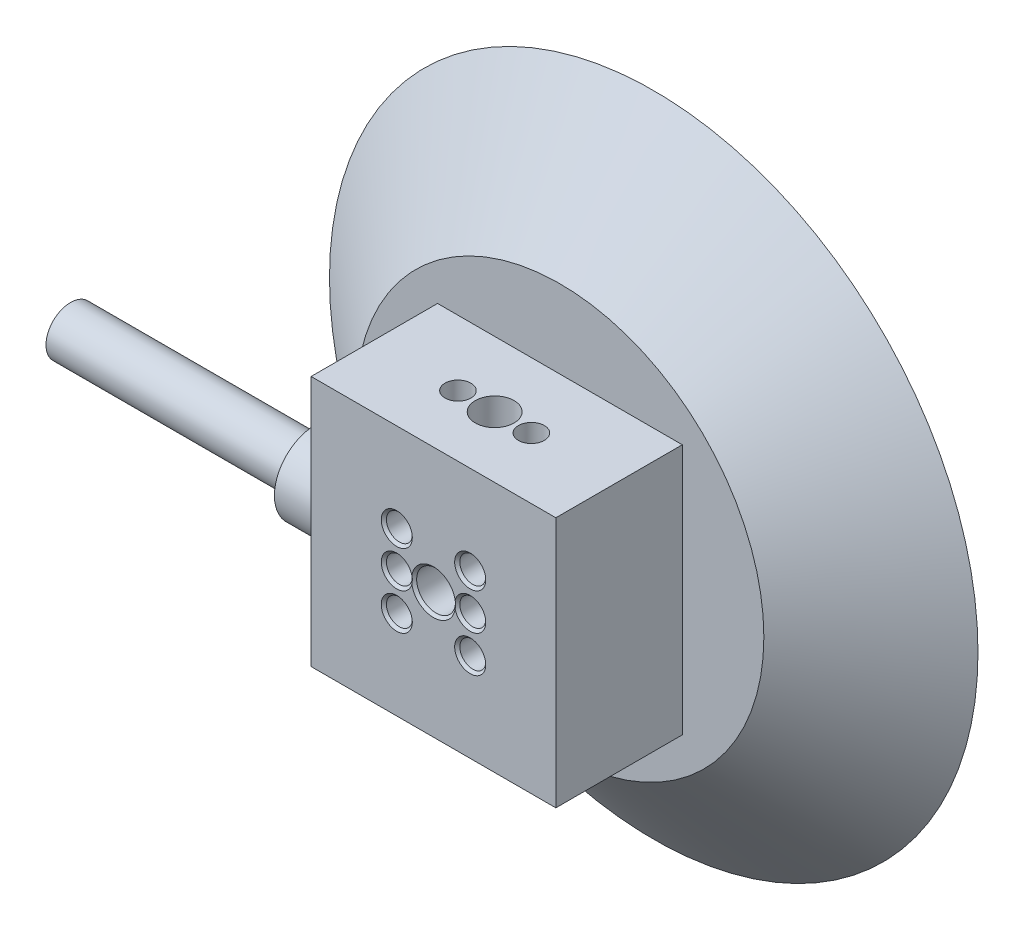
SolidWorks part; units mm, degrees
ref_plane "前视基准面" through (0, 0, 0) normal (0, 0, 1) x (1, 0, 0)
ref_plane "上视基准面" through (0, 0, 0) normal (0, 1, 0) x (1, 0, 0)
ref_plane "右视基准面" through (0, 0, 0) normal (1, 0, 0) x (0, 0, -1)
sketch "草图2" plane through (0, 0, 0) normal (0, 0, 1) x (1, 0, 0)
  circle A0 centre (0, 0) radius 79.5
  dimension "D1" = 159
ref_plane "基准面4" through (0, 0, 23) normal (0, 0, 1) x (1, 0, 0)
sketch "草图3" plane through (0, 0, 23) normal (0, 0, 1) x (1, 0, 0)
  circle A0 centre (0, 0) radius 50
  dimension "D1" = 100
loft "放样1" add profiles "草图2", "草图3"
sketch "草图4" plane through (0, 0, 23) normal (0, 0, 1) x (1, 0, 0)
  line L0 (0, 0) -> (0, -66.3516) construction
  line L1 (0, 0) -> (-87.6409, 0) construction
  line L3 (-30, 30.8) -> (30, 30.8)
  line L4 (-30, 30.8) -> (-30, -30.8)
  line L5 (-30, -30.8) -> (30, -30.8)
  line L6 (30, 30.8) -> (30, -30.8)
  dimension "D1" = 61.6
  dimension "D2" = 60
extrude "凸台-拉伸1" add sketch "草图4" along normal blind 31
sketch "草图5" plane through (-30, 0, 0) normal (-1, 0, 0) x (0, 0, 1)
  line L0 (23, 10) -> (43, 10)
  line L1 (23, -50) -> (23, 50) construction
  line L2 (20, 0) -> (77.0997, 0) construction
  line L3 (23, -10) -> (43, -10)
  line L4 (23, 10) -> (23, -10)
  arc A0 (43, -10) -> (43, 10) centre (43, 0) ccw
  dimension "D2" = 10
  dimension "D1" = 10
  dimension "D3" = 20
extrude "凸台-拉伸2" add sketch "草图5" along normal blind 10
sketch "草图6" plane through (-40, 0, 0) normal (-1, 0, 0) x (0, 0, 1)
  circle A0 centre (43, 0) radius 6
  dimension "D1" = 12
extrude "凸台-拉伸3" add sketch "草图6" along normal blind 60
hole_wizard "3/8 (0.375) 直径孔1" positions "草图7" profile "草图8" hole size "3/8" standard "ANSI Inch" end condition through all
sketch "草图7" plane through (0, 0, 54) normal (0, 0, 1) x (1, 0, 0)
  point P0 (0, 0)
sketch "草图8" plane through (0, 0, 54) normal (1, 0, 0) x (0, -1, 0)
  line L0 (0, 0) -> (0, 54.0001)
  line L1 (0, 54.0001) -> (4.7625, 54.0001)
  line L2 (4.7625, 54.0001) -> (4.7625, 0.635)
  line L3 (4.7625, 0.635) -> (5.3975, 0)
  line L5 (5.3975, 0) -> (0, 0)
  line L6 (-4.7625, 0.635) -> (-5.3975, 0) construction
  line L11 (0, -6.35) -> (0, 107.95) construction
  dimension "通孔孔直径" = 9.525
  dimension "通孔孔深度" = 54.0001
  dimension "近端锥形沉头孔直径" = 10.795
  dimension "近端锥形沉头孔角度" = 90
hole_wizard "1/4 (0.25) 直径孔1" positions "草图9" profile "草图10" hole size "1/4" standard "ANSI Inch" end condition through all
sketch "草图9" plane through (0, 0, 54) normal (0, 0, 1) x (1, 0, 0)
  line L0 (0, 30.75) -> (0, -30.75) construction
  line L4 (-30, 0) -> (30, 0) construction
  point P19 (-9, 9)
  point P21 (-9, 0)
  point P28 (-9, -9)
  point P29 (9, -9)
  point P30 (9, 0)
  point P31 (9, 9)
  dimension "D2" = 9
  dimension "D1" = 9
  dimension "D3" = 0
sketch "草图10" plane through (9, 9, 54) normal (1, 0, 0) x (0, -1, 0)
  line L0 (0, 0) -> (0, 54.0001)
  line L1 (0, 54.0001) -> (3.175, 54.0001)
  line L2 (3.175, 54.0001) -> (3.175, 0.635)
  line L3 (3.175, 0.635) -> (3.81, 0)
  line L5 (3.81, 0) -> (0, 0)
  line L6 (-3.175, 0.635) -> (-3.81, 0) construction
  line L11 (0, -6.35) -> (0, 107.95) construction
  dimension "通孔孔直径" = 6.35
  dimension "通孔孔深度" = 54.0001
  dimension "近端锥形沉头孔直径" = 7.62
  dimension "近端锥形沉头孔角度" = 90
hole_wizard "3/8 (0.375) 直径孔2" positions "草图11" profile "草图12" hole size "3/8" standard "ANSI Inch" end condition through all
sketch "草图11" plane through (0, -30.8, 0) normal (0, -1, 0) x (1, 0, 0)
  line L0 (-30, 54) -> (30, 54) construction
  point P0 (0, 39)
  dimension "D1" = 15
sketch "草图12" plane through (0, -30.8, 39) normal (1, 0, 0) x (0, 0, -1)
  line L0 (0, 0) -> (0, 110.3001)
  line L1 (0, 110.3001) -> (4.7625, 110.3001)
  line L2 (4.7625, 110.3001) -> (4.7625, 0.635)
  line L3 (4.7625, 0.635) -> (5.3975, 0)
  line L5 (5.3975, 0) -> (0, 0)
  line L6 (-4.7625, 0.635) -> (-5.3975, 0) construction
  line L11 (0, -6.35) -> (0, 107.95) construction
  dimension "通孔孔直径" = 9.525
  dimension "通孔孔深度" = 110.3001
  dimension "近端锥形沉头孔直径" = 10.795
  dimension "近端锥形沉头孔角度" = 90
hole_wizard "1/4 (0.25) 直径孔2" positions "草图13" profile "草图14" hole size "1/4" standard "ANSI Inch" end condition through all
sketch "草图13" plane through (0, -30.8, 0) normal (0, -1, 0) x (-1, 0, 0)
  line L0 (5.0784, -39) -> (-37.9132, -39) construction
  line L2 (0, -40) -> (0, -49.8506) construction
  line L3 (0, -39) -> (-19.1912, -39) construction
  point P17 (-9, -39)
  point P19 (9, -39)
  dimension "D1" = 9
  dimension "D2" = 0
sketch "草图14" plane through (-9, -30.8, 39) normal (1, 0, 0) x (0, 0, -1)
  line L0 (0, 0) -> (0, 110.3001)
  line L1 (0, 110.3001) -> (3.175, 110.3001)
  line L2 (3.175, 110.3001) -> (3.175, 0.635)
  line L3 (3.175, 0.635) -> (3.81, 0)
  line L5 (3.81, 0) -> (0, 0)
  line L6 (-3.175, 0.635) -> (-3.81, 0) construction
  line L11 (0, -6.35) -> (0, 107.95) construction
  dimension "通孔孔直径" = 6.35
  dimension "通孔孔深度" = 110.3001
  dimension "近端锥形沉头孔直径" = 7.62
  dimension "近端锥形沉头孔角度" = 90
